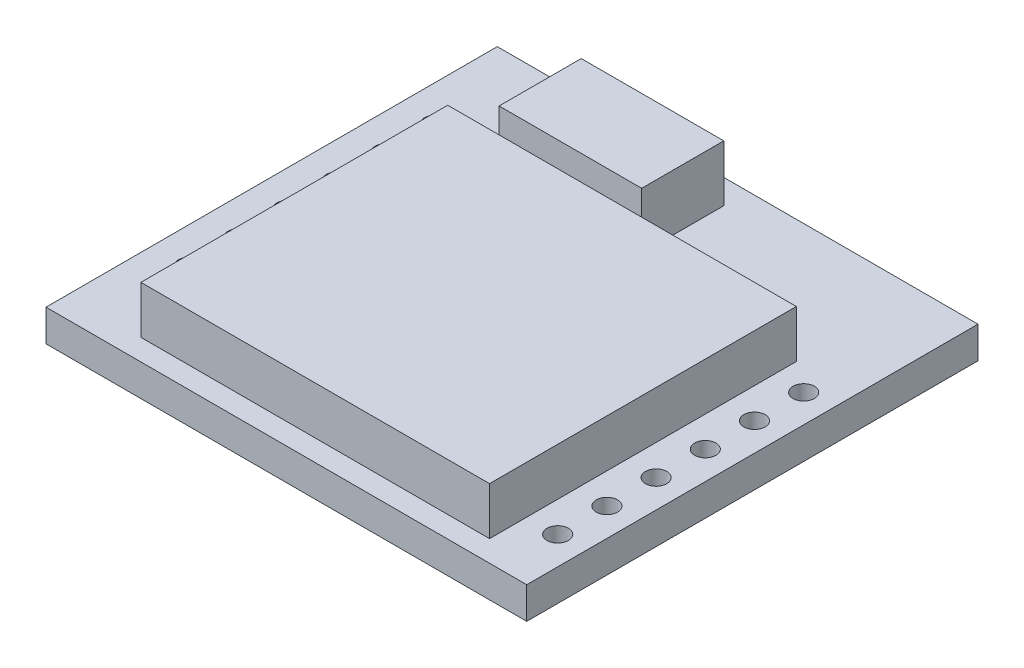
SolidWorks part; units mm, degrees
ref_plane "Plan de face" through (0, 0, 0) normal (0, 0, 1) x (1, 0, 0)
ref_plane "Plan de dessus" through (0, 0, 0) normal (0, 1, 0) x (1, 0, 0)
ref_plane "Plan de droite" through (0, 0, 0) normal (1, 0, 0) x (0, 0, -1)
sketch "Esquisse1" plane through (0, 0, 0) normal (0, 1, 0) x (1, 0, 0)
  line L0 (23.37, 28.8385) -> (23.37, -14.6556) construction
  line L1 (0, 0) -> (24.82, 0)
  line L2 (0, 0) -> (0, 23.3)
  line L3 (0, 23.3) -> (24.82, 23.3)
  line L4 (24.82, 0) -> (24.82, 23.3)
  line L5 (23.37, -14.6556) -> (1.85, -14.6556) construction
  line L6 (1.85, -14.6556) -> (1.85, 30.0204) construction
  circle A0 centre (1.85, 5.55) radius 0.55
  circle A1 centre (23.37, 3.05) radius 0.55
  circle A2 centre (1.85, 8.09) radius 0.55
  circle A3 centre (23.37, 5.59) radius 0.55
  circle A4 centre (1.85, 10.63) radius 0.55
  circle A5 centre (23.37, 8.13) radius 0.55
  circle A6 centre (1.85, 13.17) radius 0.55
  circle A7 centre (23.37, 10.67) radius 0.55
  circle A8 centre (1.85, 15.71) radius 0.55
  circle A9 centre (23.37, 13.21) radius 0.55
  circle A10 centre (1.85, 18.25) radius 0.55
  circle A11 centre (23.37, 15.75) radius 0.55
  dimension "D4" = 1.1
  dimension "D6" = 1.1
  dimension "D1" = 24.82
  dimension "D2" = 23.3
  dimension "D3" = 1.85
  dimension "D5" = 1.45
  dimension "D7" = 5.55
  dimension "D8" = 3.05
  dimension "D9" = 6
extrude "Boss.-Extru.1" add sketch "Esquisse1" along normal blind 1.64
sketch "Esquisse2" plane through (0, 1.64, 0) normal (0, 1, 0) x (1, 0, 0)
  line L0 (0, 0) -> (24.82, 0) construction
  line L1 (3.8, 16.94) -> (21.8, 16.94)
  line L2 (3.8, 16.94) -> (3.8, 1.1)
  line L3 (3.8, 1.1) -> (21.8, 1.1)
  line L4 (21.8, 16.94) -> (21.8, 1.1)
  line L5 (0, 23.3) -> (0, 0) construction
  dimension "D1" = 18
  dimension "D2" = 15.84
  dimension "D3" = 1.1
  dimension "D4" = 3.8
extrude "Boss.-Extru.2" add sketch "Esquisse2" along normal blind 2.46
sketch "Esquisse3" plane through (0, 1.64, 0) normal (0, 1, 0) x (1, 0, 0)
  line L1 (5.6014, 22.0343) -> (12.9614, 22.0343)
  line L2 (5.6014, 22.0343) -> (5.6014, 17.7943)
  line L3 (5.6014, 17.7943) -> (12.9614, 17.7943)
  line L4 (12.9614, 22.0343) -> (12.9614, 17.7943)
  dimension "D1" = 4.24
  dimension "D2" = 7.36
extrude "Boss.-Extru.3" add sketch "Esquisse3" along normal blind 2.9
sketch "Esquisse4" plane through (0, 0, 0) normal (0, -1, 0) x (1, 0, 0)
  line L0 (24.82, -23.3) -> (0, -23.3) construction
  line L1 (4.92, -7.6) -> (20.22, -7.6)
  line L2 (4.92, -7.6) -> (4.92, -23.3)
  line L3 (4.92, -23.3) -> (20.22, -23.3)
  line L4 (20.22, -7.6) -> (20.22, -23.3)
  line L5 (24.82, 0) -> (24.82, -23.3) construction
  line L6 (20.22, -7.6) -> (15.72, -7.6)
  line L7 (20.22, -7.6) -> (20.22, -6.2)
  line L8 (20.22, -6.2) -> (15.72, -6.2)
  line L9 (15.72, -7.6) -> (15.72, -6.2)
  line M8 (0, -23.3) -> (24.82, -23.3)
  dimension "D1" = 15.3
  dimension "D2" = 15.7
  dimension "D3" = 1.4
  dimension "D4" = 4.5
  dimension "D5" = 4.6
extrude "Boss.-Extru.4" add sketch "Esquisse4" along normal blind 1.4 contours L4 L1 L2 M8 | L9 L1 L7 L8
